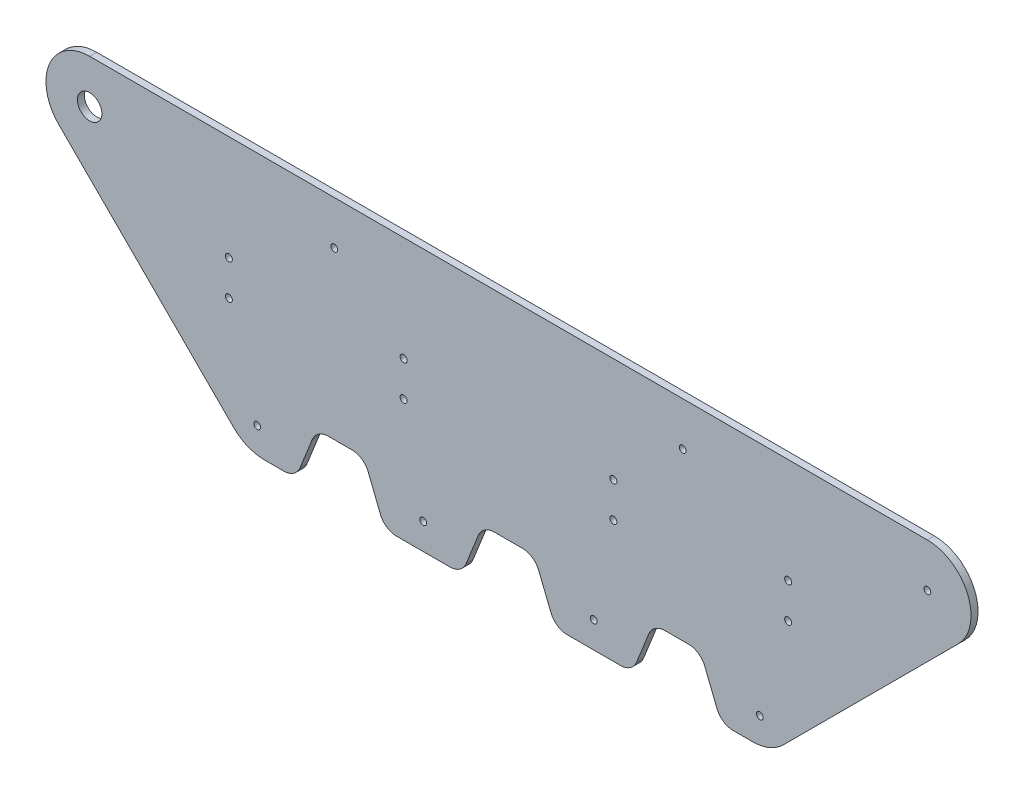
SolidWorks part; units mm, degrees
ref_plane "前视基准面" through (0, 0, 0) normal (0, 0, 1) x (1, 0, 0)
ref_plane "上视基准面" through (0, 0, 0) normal (0, 1, 0) x (1, 0, 0)
ref_plane "右视基准面" through (0, 0, 0) normal (1, 0, 0) x (0, 0, -1)
sketch "草图1" plane through (0, 0, 0) normal (0, 0, 1) x (1, 0, 0)
  line L0 (-7.3223, 7.3223) -> (-107.3223, 107.3223)
  line L1 (-89.6447, 150) -> (389.6447, 150)
  line L2 (407.3223, 107.3223) -> (307.3223, 7.3223)
  line L3 (289.6447, 0) -> (10.3553, 0)
  arc A0 (307.3223, 7.3223) -> (289.6447, 0) centre (289.6447, 25) cw
  arc A1 (-7.3223, 7.3223) -> (10.3553, 0) centre (10.3553, 25) ccw
  arc A2 (389.6447, 150) -> (407.3223, 107.3223) centre (389.6447, 125) cw
  arc A3 (-107.3223, 107.3223) -> (-89.6447, 150) centre (-89.6447, 125) cw
  circle A8 centre (50.3553, 125) radius 1.95
  circle A9 centre (249.6447, 125) radius 1.95
  circle A11 centre (101.2132, 15) radius 1.95
  circle A12 centre (198.7868, 15) radius 1.95
  circle A13 centre (-89.6447, 125) radius 7
  circle A14 centre (6.2132, 15) radius 1.95
  circle A15 centre (293.7868, 15) radius 1.95
  circle A16 centre (389.6447, 125) radius 1.95
  point P7 (300, 0)
  point P10 (0, 0)
  dimension "D4" = 25
  dimension "D5" = 15
  dimension "D6" = 3.9
  dimension "D7" = 140
  dimension "D12" = 15
  dimension "D13" = 14
  dimension "D1" = 300
  dimension "D2" = 135
  dimension "D3" = 150
  dimension "D8" = 140
  dimension "D9" = 95
  dimension "D10" = 95
  dimension "D11" = 15
extrude "凸台-拉伸1" add sketch "草图1" along normal blind 4
sketch "草图2" plane through (0, 0, 4) normal (0, 0, 1) x (1, 0, 0)
  line L0 (389.6447, 150) -> (-89.6447, 150) construction
  line L1 (389.6447, 150) -> (-89.6447, 150) construction
  circle A0 centre (-10, 90) radius 2
  circle A1 centre (90, 90) radius 2
  circle A2 centre (210, 90) radius 2
  circle A3 centre (310, 90) radius 2
  circle A4 centre (-10, 70) radius 2
  circle A5 centre (90, 70) radius 2
  circle A6 centre (210, 70) radius 2
  circle A7 centre (310, 70) radius 2
  point P10 (150, 150)
  dimension "D6" = 4
  dimension "D1" = 60
  dimension "D2" = 120
  dimension "D3" = 100
  dimension "D4" = 100
  dimension "D5" = 60
  dimension "D7" = 20
extrude "切除-拉伸1" cut sketch "草图2" against normal blind 10
sketch "草图3" plane through (0, 0, 4) normal (0, 0, 1) x (1, 0, 0)
  line L0 (28.2132, 0) -> (40.2132, 30)
  line L1 (10.3553, 0) -> (289.6447, 0) construction
  line L2 (40.2132, 30) -> (67.2132, 30)
  line L3 (67.2132, 30) -> (79.2132, 0)
  line L4 (79.2132, 0) -> (28.2132, 0)
  line L5 (123.2132, 0) -> (135.2132, 30)
  line L6 (135.2132, 30) -> (164.7868, 30)
  line L7 (164.7868, 30) -> (176.7868, 0)
  line L8 (176.7868, 0) -> (123.2132, 0)
  line L9 (220.7868, 0) -> (232.7868, 30)
  line L10 (232.7868, 30) -> (259.7868, 30)
  line L11 (259.7868, 30) -> (271.7868, 0)
  line L12 (271.7868, 0) -> (220.7868, 0)
  circle A0 centre (6.2132, 15) radius 1.95 construction
  circle A1 centre (101.2132, 15) radius 1.95 construction
  circle A2 centre (198.7868, 15) radius 1.95 construction
  circle A3 centre (293.7868, 15) radius 1.95 construction
  dimension "D1" = 30
  dimension "D2" = 12
  dimension "D3" = 12
  dimension "D4" = 12
  dimension "D5" = 12
  dimension "D6" = 12
  dimension "D7" = 12
  dimension "D8" = 22
  dimension "D9" = 22
  dimension "D10" = 22
  dimension "D11" = 22
  dimension "D12" = 22
  dimension "D13" = 22
extrude "切除-拉伸2" cut sketch "草图3" against normal blind 10
fillet "圆角1" radius 10 12 edges at (259.7868, 30, 2) (164.7868, 30, 2) (67.2132, 30, 2) (271.7868, 0, 2) (232.7868, 30, 2) (220.7868, 0, 2) (176.7868, 0, 2) (123.2132, 0, 2) (135.2132, 30, 2) (40.2132, 30, 2) (79.2132, 0, 2) (28.2132, 0, 2)
